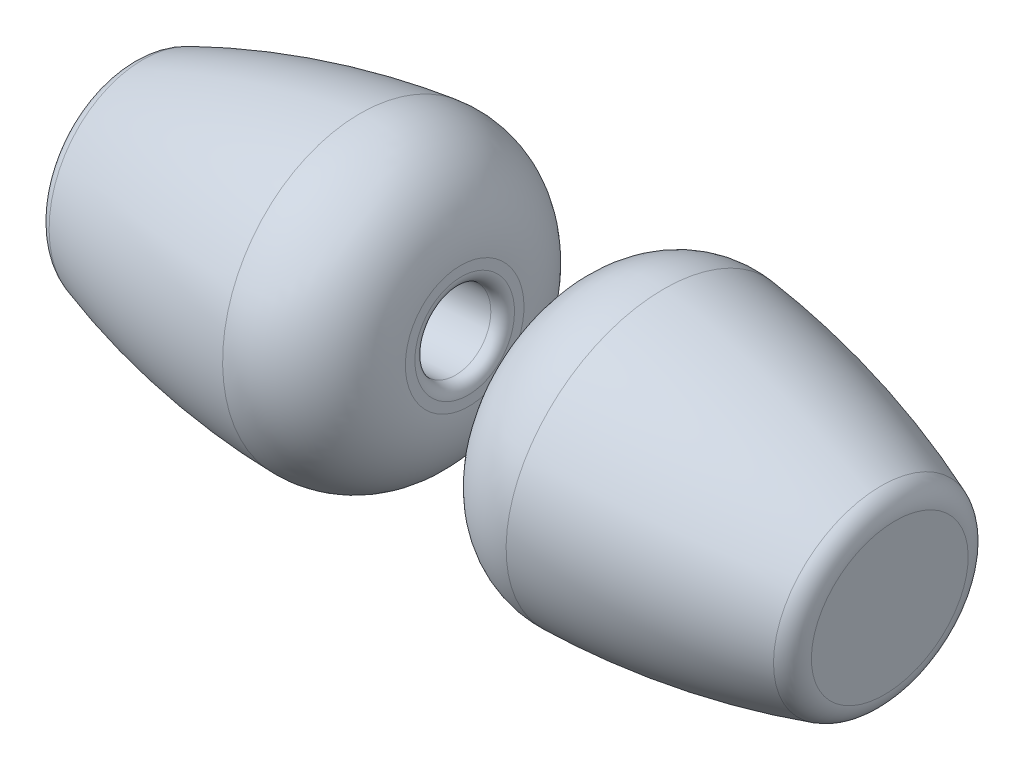
SolidWorks part; units mm, degrees
ref_plane "Alzado" through (0, 0, 0) normal (0, 0, 1) x (1, 0, 0)
ref_plane "Planta" through (0, 0, 0) normal (0, 1, 0) x (1, 0, 0)
ref_plane "Vista lateral" through (0, 0, 0) normal (1, 0, 0) x (0, 0, -1)
sketch "Croquis1" plane through (0, 0, 0) normal (0, 0, 1) x (1, 0, 0)
  line L0 (0, 0) -> (0, 191.7552) construction
  line L1 (5, 160.1093) -> (40.914, 157.6226) construction
  line L2 (40.914, 157.6226) -> (30, 0) construction
  line L3 (27.506, 0.1727) -> (38.5804, 160.1115) construction
  line L4 (27.506, 0.1727) -> (30, 0) construction
  line L5 (5, 160.1093) -> (4.8273, 157.6153) construction
  line L6 (4.8273, 157.6153) -> (-19.3231, 159.2875) construction
  line L7 (24.0182, -50.199) -> (31.2919, 54.8506) construction
  circle A0 centre (27.506, 0.1727) radius 2.5 construction
  spline S0 degree 3 poles (4.8273, 157.6153) (36.4183, 155.4279) (39.0186, 166.4413) (27.506, 0.1727) knots 0 0 0 0 1 1 1 1
  dimension "D5" = 5
  dimension "D6" = 95
  dimension "D7" = 500
  dimension "D1" = 30
  dimension "D2" = 10
  dimension "D3" = 36
  dimension "D4" = 158
ref_plane "Plano1" through (27.506, 0.1727, 0) normal (-0.0691, -0.9976, 0) x (-0.9976, 0.0691, 0)
sketch "Croquis2" plane through (27.506, 0.1727, 0) normal (-0.0691, -0.9976, 0) x (-0.9976, 0.0691, 0)
  circle A0 centre (0, 0) radius 2.5
  dimension "D1" = 5
sketch "Croquis9" plane through (0, 0, 0) normal (0, 0, 1) x (1, 0, 0)
  line L0 (2, 157.8111) -> (2.1727, 160.3051)
  line L1 (4.8273, 157.6153) -> (-19.3231, 159.2875) construction
  line L2 (6.4204, 163.7449) -> (16.2429, 160.8345) construction
  line L3 (16.2429, 160.8345) -> (15.9666, 156.844)
  line L4 (15.9666, 156.844) -> (2, 157.8111)
  line L5 (0, 0) -> (0, 191.7552) construction
  line L6 (6.4204, 163.7449) -> (5.9904, 157.5348) construction
  arc A0 (6.4204, 163.7449) -> (2.1727, 160.3051) centre (5.8982, 160.0471) ccw
  arc A1 (16.2429, 160.8345) -> (6.4204, 163.7449) centre (1.5553, 129.2956) ccw
  dimension "D1" = 2
  dimension "D2" = 6.225
  dimension "D3" = 4
  dimension "D4" = 14
  dimension "D5" = 10
  dimension "D6" = 2.5
revolve "Revolución1" add sketch "Croquis9" angle 360 about L4
fillet "Redondeo1" radius 1 1 edges at (16.2429, 160.8345, 0)
sketch "Croquis10" plane through (-8.8845, 0.6152, 0) normal (-0.9976, 0.0691, 0) x (0, 0, 1)
  circle A0 centre (0, 157.5723) radius 1.6
  circle A1 centre (0, 157.5723) radius 2.5 construction
  dimension "D1" = 3.2
extrude "Cortar-Extruir2" cut sketch "Croquis10" against normal blind 10
fillet "Redondeo2" radius 0.5 1 edges at (1.8895, 156.2149, 0)
mirror "Simetría6" about plane through (0, 0, 0) normal (1, 0, 0) of bodies 135
